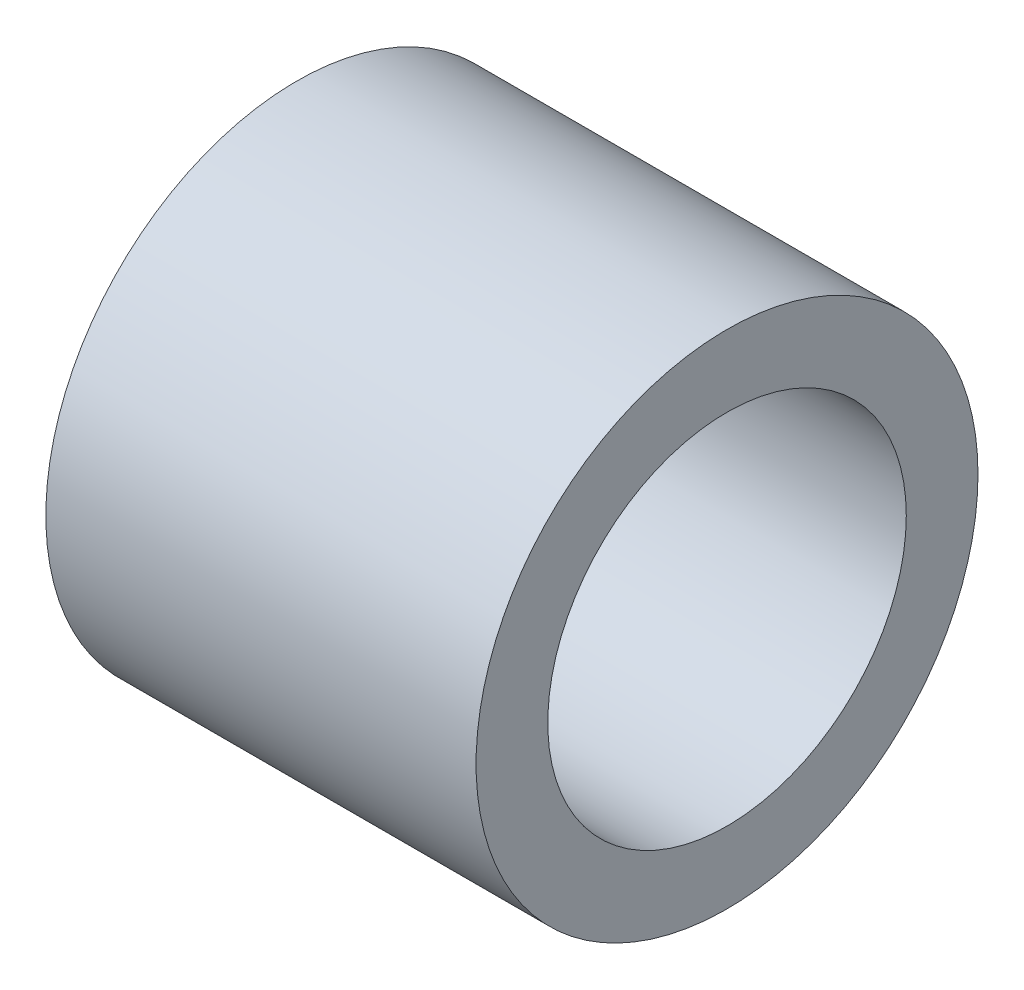
SolidWorks part; units mm, degrees
ref_plane "Front Plane" through (0, 0, 0) normal (0, 0, 1) x (1, 0, 0)
ref_plane "Top Plane" through (0, 0, 0) normal (0, 1, 0) x (1, 0, 0)
ref_plane "Right Plane" through (0, 0, 0) normal (1, 0, 0) x (0, 0, -1)
sketch "Sketch1" plane through (0, 0, 0) normal (1, 0, 0) x (0, 0, -1)
  circle A0 centre (0, 0) radius 10
  dimension "D1" = 20
extrude "Extrude-Thin1" add sketch "Sketch1" along normal blind 24 thin
